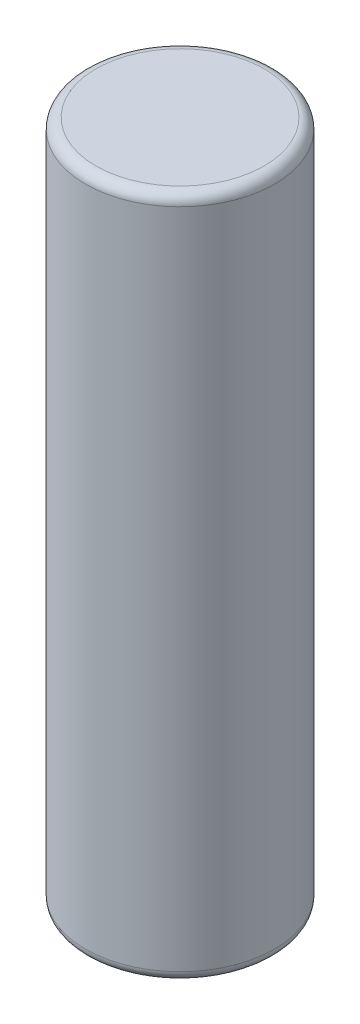
SolidWorks part; units mm, degrees
ref_plane "Front Plane" through (0, 0, 0) normal (0, 0, 1) x (1, 0, 0)
ref_plane "Top Plane" through (0, 0, 0) normal (0, 1, 0) x (1, 0, 0)
ref_plane "Right Plane" through (0, 0, 0) normal (1, 0, 0) x (0, 0, -1)
sketch "Sketch1" plane through (0, 0, 0) normal (0, 1, 0) x (1, 0, 0)
  circle A0 centre (0, 0) radius 9
  dimension "D1" = 18
extrude "Boss-Extrude1" add sketch "Sketch1" along normal blind 65
fillet "Fillet1" radius 1 2 edges at (0, 0, 9) (0, 65, 9)
